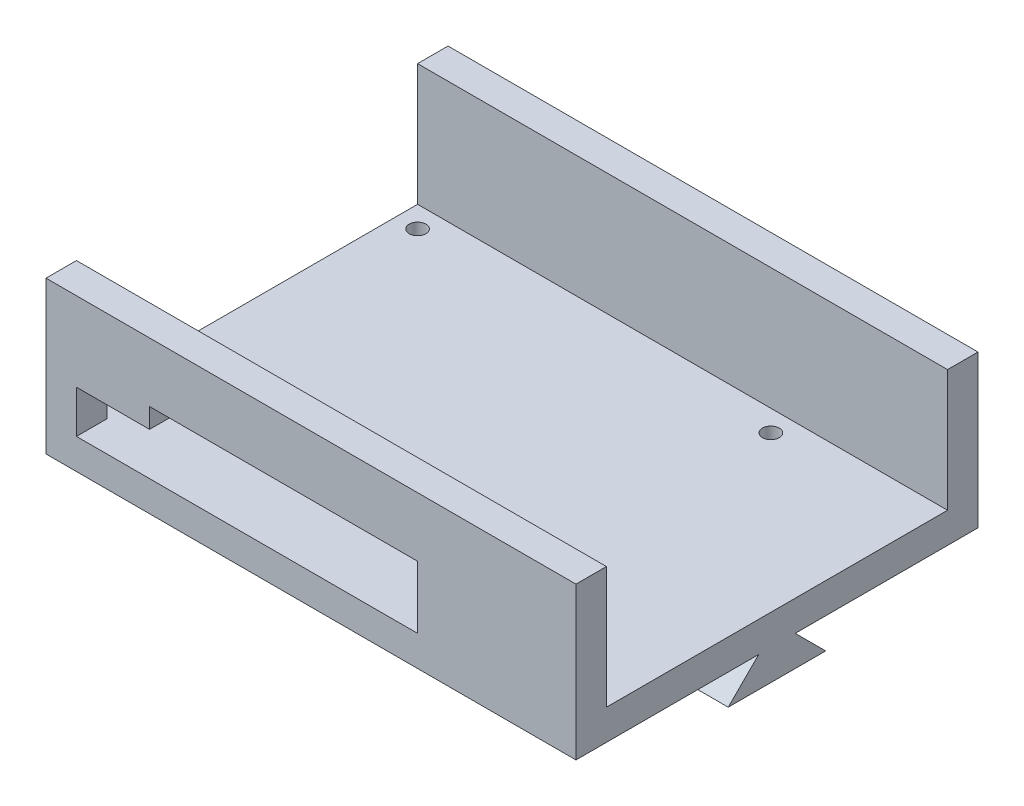
SolidWorks part; units mm, degrees
ref_plane "Спереди" through (0, 0, 0) normal (0, 0, 1) x (1, 0, 0)
ref_plane "Сверху" through (0, 0, 0) normal (0, 1, 0) x (1, 0, 0)
ref_plane "Справа" through (0, 0, 0) normal (1, 0, 0) x (0, 0, -1)
sketch "Sketch1" plane through (0, 0, 0) normal (0, 1, 0) x (1, 0, 0)
  line L1 (-43.5, 33) -> (43.5, 33)
  line L2 (-43.5, 33) -> (-43.5, -33)
  line L3 (-43.5, -33) -> (43.5, -33)
  line L4 (43.5, 33) -> (43.5, -33)
  line L5 (-43.5, 33) -> (43.5, -33) construction
  line L6 (-43.5, -33) -> (43.5, 33) construction
  circle A0 centre (-40, 24.5) radius 1.375
  circle A1 centre (-40, -24.5) radius 1.375
  circle A2 centre (18, 24.5) radius 1.375
  circle A3 centre (18, -24.5) radius 1.375
  point P0 (0, 0)
  dimension "D3" = 40
  dimension "D5" = 40
  dimension "D7" = 49
  dimension "D4" = 58
  dimension "D6" = 49
  dimension "D1" = 66
  dimension "D2" = 87
extrude "Boss-Extrude1" add sketch "Sketch1" along normal blind 10
sketch "Sketch2" plane through (0, 0, 0) normal (1, 0, 0) x (0, 0, -1)
  line L0 (-1000, 0) -> (49000, 0) construction
  line L1 (0, -1000) -> (0, 49000) construction
  line L2 (-1000, 10) -> (49000, 10) construction
  line L3 (33, 10) -> (-33, 10) construction
  line L4 (33, 5) -> (3, 5)
  line L5 (-972, 5) -> (49028, 5) construction
  line L6 (33, 10) -> (33, 0) construction
  line L7 (-33, 5) -> (-3, 5)
  line L8 (-33, 10) -> (-33, 0) construction
  line L9 (-3, 5) -> (-8, 0)
  line L10 (-8, 0) -> (-33, 0)
  line L11 (-33, 0) -> (-33, 5)
  line L12 (3, 5) -> (8, 0)
  line L13 (8, 0) -> (33, 0)
  line L14 (33, 0) -> (33, 5)
  point P10 (0, 10)
  point P17 (33, 5)
extrude "Cut-Extrude1" cut sketch "Sketch2" against normal through all both and the other way through all
sketch "Sketch3" plane through (0, 0, 0) normal (1, 0, 0) x (0, 0, -1)
  line L0 (0, -1000) -> (0, 49000) construction
  line L1 (-1000, 10) -> (49000, 10) construction
  line L2 (33, 10) -> (-33, 10) construction
  line L3 (33, 10) -> (33, 30)
  line L4 (33, 30) -> (28, 30)
  line L5 (28, 30) -> (28, 10)
  line L6 (-33, 10) -> (-33, 30)
  line L7 (-33, 30) -> (-28, 30)
  line L8 (-28, 30) -> (-28, 10)
  line L9 (-28, 10) -> (-33, 10)
  line L10 (28, 10) -> (33, 10)
  point P8 (0, 10)
extrude "Boss-Extrude2" add sketch "Sketch3" along normal through all and the other way through all
ref_plane "Plane1" through (0, 0, 33) normal (0, 0, 1) x (1, 0, 0)
sketch "Sketch4" plane through (0, 0, 33) normal (0, 0, 1) x (1, 0, 0)
  line L0 (0, 0) -> (0, 50000) construction
  line L1 (-1000, 5) -> (49000, 5) construction
  line L2 (-43.5, 5) -> (43.5, 5) construction
  line L3 (-1000, 10) -> (49000, 10) construction
  line L4 (-43.5, -985.7019) -> (-43.5, 49014.2981) construction
  line L5 (-26.5, 17) -> (-26.5, 20.2507)
  line L6 (-38.5, 10) -> (-38.5, 17)
  line L7 (-38.5, 17) -> (-26.5, 17)
  line L9 (-26.5, 10) -> (-38.5, 10)
  line L10 (-26.5, 20.2507) -> (17.5, 20.2507)
  line L11 (17.5, 20.2507) -> (17.5, 10)
  line L12 (17.5, 10) -> (-26.5, 10)
  line L13 (43.5, 17.5) -> (43.5, -49982.5) construction
  line L14 (43.5, 30) -> (43.5, 5) construction
  point P8 (0, 5)
  point P25 (43.5, 17.5)
  dimension "D1" = 5
  dimension "D2" = 5
  dimension "D4" = 7
  dimension "D5" = 26
extrude "Cut-Extrude2" cut sketch "Sketch4" against normal blind 10
